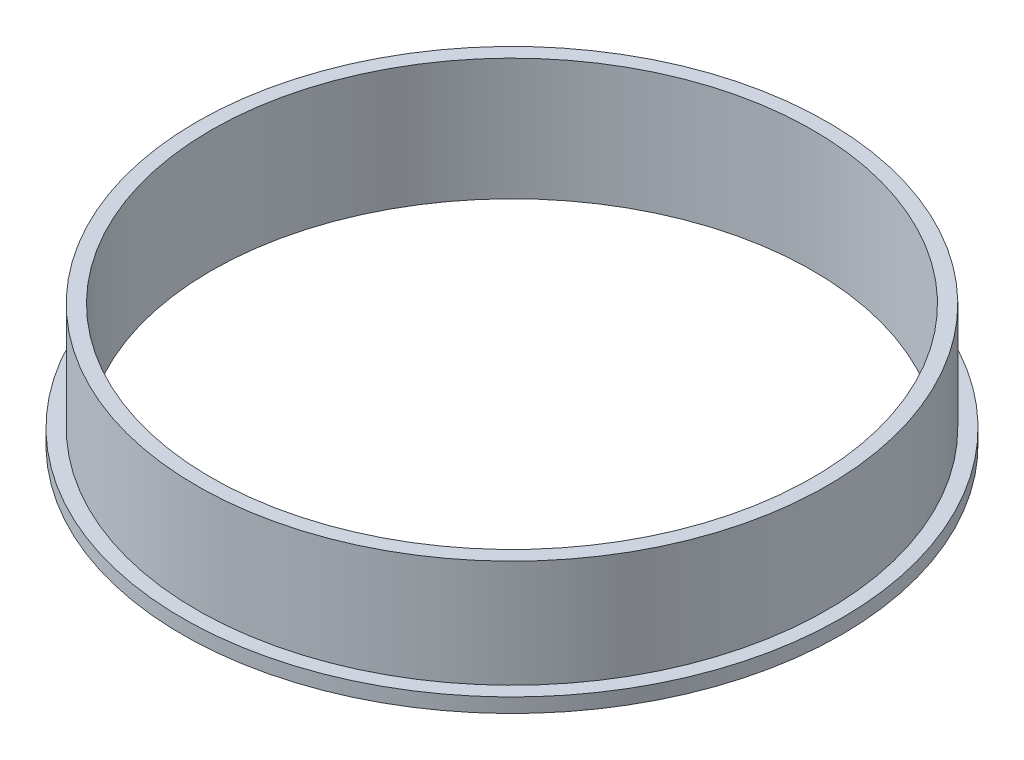
SolidWorks part; units mm, degrees
ref_plane "Front Plane" through (0, 0, 0) normal (0, 0, 1) x (1, 0, 0)
ref_plane "Top Plane" through (0, 0, 0) normal (0, 1, 0) x (1, 0, 0)
ref_plane "Right Plane" through (0, 0, 0) normal (1, 0, 0) x (0, 0, -1)
sketch "Sketch1" plane through (0, 0, 0) normal (0, 0, 1) x (1, 0, 0)
  line L17 (0, 15.8556) -> (0, -8.6801)
  line L20 (-44, 24) -> (-42, 24)
  line L22 (-42, 24) -> (-42, 7)
  line L23 (-42, 7) -> (-46, 7)
  line L24 (-46, 7) -> (-46, 9)
  line L25 (-46, 9) -> (-44, 9)
  line L26 (-44, 9) -> (-44, 24)
  dimension "D8" = 2
  dimension "D9" = 17
  dimension "D10" = 4
  dimension "D14" = 2
  dimension "D15" = 15
  dimension "D21" = 0
revolve "Revolve1" add sketch "Sketch1" angle 360 about L17
